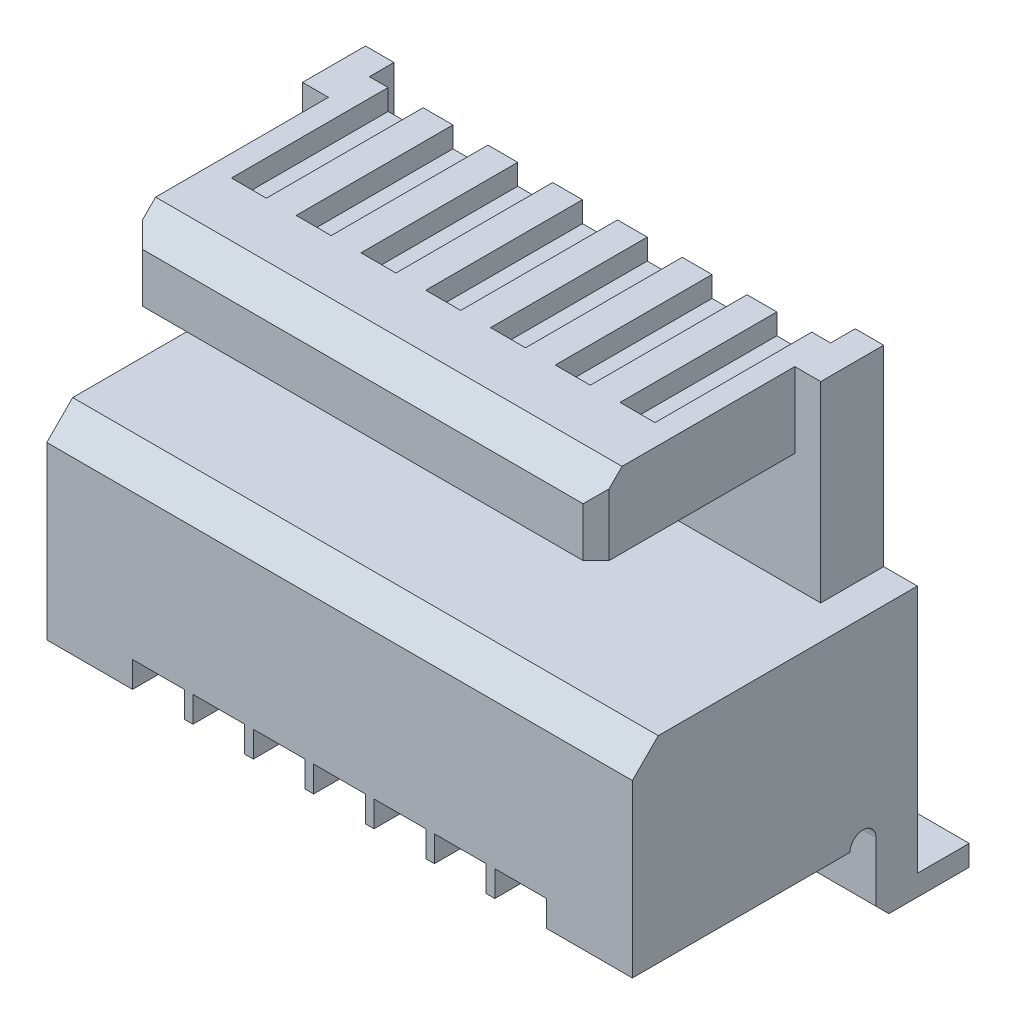
SolidWorks part; units mm, degrees
ref_plane "Front Plane" through (0, 0, 0) normal (0, 0, 1) x (1, 0, 0)
ref_plane "Top Plane" through (0, 0, 0) normal (0, 1, 0) x (1, 0, 0)
ref_plane "Right Plane" through (0, 0, 0) normal (1, 0, 0) x (0, 0, -1)
sketch "Sketch1" plane through (0, 0, 0) normal (0, 1, 0) x (1, 0, 0)
  line L0 (0, 0) -> (0, -11)
  line L1 (0, -11) -> (22.6, -11)
  line L2 (22.6, -11) -> (22.6, 0)
  line L3 (0, 0) -> (2.8, 0)
  line L4 (2.8, 0) -> (2.8, -8.9)
  line L5 (2.8, -8.9) -> (19.8, -8.9)
  line L6 (19.8, -8.9) -> (19.8, 0)
  line L7 (19.8, 0) -> (22.6, 0)
  dimension "D1" = 11
  dimension "D2" = 22.6
  dimension "D3" = 2.8
  dimension "D4" = 2.8
  dimension "D5" = 2.1
  dimension "D6" = 11
extrude "Boss-Extrude1" add sketch "Sketch1" along normal blind 7.6
sketch "Sketch2" plane through (0, 7.6, 0) normal (0, 1, 0) x (1, 0, 0)
  line L0 (2.8, 0) -> (19.8, 0)
  line L1 (2.8, 0) -> (2.8, -8.9)
  line L2 (2.8, -8.9) -> (19.8, -8.9)
  line L3 (19.8, -8.9) -> (19.8, 0)
  line L8 (2.8, 0) -> (0, 0)
  line L9 (0, 0) -> (0, -11)
  line L10 (0, -11) -> (22.6, -11)
  line L11 (22.6, -11) -> (22.6, 0)
  line L12 (22.6, 0) -> (19.8, 0)
  line L13 (19.8, 0) -> (19.8, -8.9)
  line L14 (19.8, -8.9) -> (2.8, -8.9)
  line L15 (2.8, -8.9) -> (2.8, 0)
  line L16 (2.8, 0) -> (0, 0)
  line L17 (0, 0) -> (0, -11)
  line L18 (0, -11) -> (22.6, -11)
  line L19 (22.6, -11) -> (22.6, 0)
  line L20 (22.6, 0) -> (19.8, 0)
  line L21 (19.8, 0) -> (19.8, -8.9)
  line L22 (19.8, -8.9) -> (2.8, -8.9)
  line L23 (2.8, -8.9) -> (2.8, 0)
  line M14 (19.8, 0) -> (19.8, -8.9)
  line M15 (19.8, -8.9) -> (2.8, -8.9)
  line M16 (2.8, -8.9) -> (2.8, 0)
  dimension "D1" = 0
extrude "Boss-Extrude2" add sketch "Sketch2" against normal blind 2 contours L0 M16 M15 M14
sketch "Sketch3" plane through (0, 7.6, 0) normal (0, 1, 0) x (1, 0, 0)
  line L1 (1.3, -2.43) -> (21.3, -2.43)
  line L2 (1.3, -2.43) -> (1.3, 0)
  line L4 (22.6, 0) -> (0, 0)
  line L5 (0, 0) -> (0, -11)
  line L6 (0, -11) -> (22.6, -11)
  line L7 (22.6, -11) -> (22.6, 0)
  line L8 (22.6, 0) -> (0, 0)
  line L9 (0, 0) -> (0, -11)
  line L10 (0, -11) -> (22.6, -11)
  line L11 (22.6, -11) -> (22.6, 0)
  line L12 (21.3, -2.43) -> (21.3, 0)
  line L13 (1.3, -2.43) -> (11.3, 0) construction
  line L14 (11.3, 0) -> (21.3, -2.43) construction
  point P2 (11.3, 0)
  dimension "D2" = 20
  dimension "D3" = 2.43
  dimension "D4" = 10
  dimension "D1" = 0
extrude "Boss-Extrude3" add sketch "Sketch3" along normal blind 7.4 contours L1 L12 L8 L2
sketch "Sketch4" plane through (0, 0, 2.43) normal (0, 0, 1) x (1, 0, 0)
  line L0 (2.3, 15) -> (2.3, 12.1)
  line L1 (2.3, 12.1) -> (20.3, 12.1)
  line L2 (20.3, 12.1) -> (20.3, 15)
  line L4 (1.3, 7.6) -> (21.3, 7.6)
  line L5 (21.3, 7.6) -> (21.3, 15)
  line L6 (21.3, 15) -> (1.3, 15)
  line L7 (1.3, 15) -> (1.3, 7.6)
  line L8 (1.3, 7.6) -> (21.3, 7.6)
  line L9 (21.3, 7.6) -> (21.3, 15)
  line L10 (21.3, 15) -> (1.3, 15)
  line L11 (1.3, 15) -> (1.3, 7.6)
  point P6 (11.3, 15)
  line M10 (21.3, 15) -> (1.3, 15)
  dimension "D2" = 9
  dimension "D3" = 18
  dimension "D4" = 2.9
  dimension "D1" = 0
extrude "Boss-Extrude4" add sketch "Sketch4" along normal blind 7.67 contours L1 L2 L0 M10
sketch "Sketch5" plane through (0, 0, 0) normal (0, 0, -1) x (-1, 0, 0)
  line L0 (-19.8, 5.6) -> (-19.8, 11.5)
  line L1 (-19.8, 11.5) -> (-20.2, 11.5)
  line L2 (-20.2, 11.5) -> (-20.2, 15)
  line L3 (-2.8, 5.6) -> (-2.8, 11.5)
  line L4 (-2.8, 11.5) -> (-2.4, 11.5)
  line L5 (-2.4, 11.5) -> (-2.4, 15)
  line L12 (-22.6, 0) -> (-19.8, 0)
  line L13 (-19.8, 0) -> (-19.8, 5.6)
  line L14 (-19.8, 5.6) -> (-2.8, 5.6)
  line L15 (-2.8, 5.6) -> (-2.8, 0)
  line L16 (-2.8, 0) -> (0, 0)
  line L17 (0, 0) -> (0, 7.6)
  line L18 (0, 7.6) -> (-1.3, 7.6)
  line L19 (-1.3, 7.6) -> (-1.3, 15)
  line L20 (-1.3, 15) -> (-21.3, 15)
  line L21 (-21.3, 15) -> (-21.3, 7.6)
  line L22 (-21.3, 7.6) -> (-22.6, 7.6)
  line L23 (-22.6, 7.6) -> (-22.6, 0)
  line L24 (-22.6, 0) -> (-19.8, 0)
  line L25 (-19.8, 0) -> (-19.8, 5.6)
  line L26 (-19.8, 5.6) -> (-2.8, 5.6)
  line L27 (-2.8, 5.6) -> (-2.8, 0)
  line L28 (-2.8, 0) -> (0, 0)
  line L29 (0, 0) -> (0, 7.6)
  line L30 (0, 7.6) -> (-1.3, 7.6)
  line L31 (-1.3, 7.6) -> (-1.3, 15)
  line L32 (-1.3, 15) -> (-21.3, 15)
  line L33 (-21.3, 15) -> (-21.3, 7.6)
  line L34 (-21.3, 7.6) -> (-22.6, 7.6)
  line L35 (-22.6, 7.6) -> (-22.6, 0)
  line M19 (-19.8, 5.6) -> (-2.8, 5.6)
  line M25 (-1.3, 15) -> (-21.3, 15)
  dimension "D2" = 1.1
  dimension "D3" = 3.5
  dimension "D4" = 1.1
  dimension "D5" = 3.5
  dimension "D1" = 0
extrude "Cut-Extrude1" cut sketch "Sketch5" against normal blind 0.95 contours L4 L5 L2 L1 L0 L3 M25 M19
sketch "Sketch6" plane through (0, 15, 0) normal (0, 1, 0) x (1, 0, 0)
  line L0 (3.125, -0.95) -> (3.125, -7)
  line L1 (3.125, -7) -> (4.475, -7)
  line L2 (4.475, -7) -> (4.475, -0.95)
  line L3 (5.625, -0.95) -> (5.625, -7)
  line L4 (5.625, -7) -> (6.975, -7)
  line L5 (6.975, -7) -> (6.975, -0.95)
  line L6 (8.125, -0.95) -> (8.125, -7)
  line L7 (8.125, -7) -> (9.475, -7)
  line L8 (9.475, -7) -> (9.475, -0.95)
  line L9 (10.625, -0.95) -> (10.625, -7)
  line L10 (10.625, -7) -> (11.975, -7)
  line L11 (11.975, -7) -> (11.975, -0.95)
  line L12 (21.3, 0) -> (20.2, 0)
  line L13 (20.2, 0) -> (20.2, -0.95)
  line L14 (20.2, -0.95) -> (2.4, -0.95)
  line L15 (2.4, -0.95) -> (2.4, 0)
  line L16 (2.4, 0) -> (1.3, 0)
  line L17 (1.3, 0) -> (1.3, -2.43)
  line L18 (1.3, -2.43) -> (2.3, -2.43)
  line L19 (2.3, -2.43) -> (2.3, -10.1)
  line L20 (2.3, -10.1) -> (20.3, -10.1)
  line L21 (20.3, -10.1) -> (20.3, -2.43)
  line L22 (20.3, -2.43) -> (21.3, -2.43)
  line L23 (21.3, -2.43) -> (21.3, 0)
  line L24 (21.3, 0) -> (20.2, 0)
  line L25 (20.2, 0) -> (20.2, -0.95)
  line L26 (20.2, -0.95) -> (2.4, -0.95)
  line L27 (2.4, -0.95) -> (2.4, 0)
  line L28 (2.4, 0) -> (1.3, 0)
  line L29 (1.3, 0) -> (1.3, -2.43)
  line L30 (1.3, -2.43) -> (2.3, -2.43)
  line L31 (2.3, -2.43) -> (2.3, -10.1)
  line L32 (2.3, -10.1) -> (20.3, -10.1)
  line L33 (20.3, -10.1) -> (20.3, -2.43)
  line L34 (20.3, -2.43) -> (21.3, -2.43)
  line L35 (21.3, -2.43) -> (21.3, 0)
  line L36 (13.125, -0.95) -> (13.125, -7)
  line L37 (13.125, -7) -> (14.475, -7)
  line L38 (14.475, -7) -> (14.475, -0.95)
  line L39 (15.625, -0.95) -> (15.625, -7)
  line L40 (15.625, -7) -> (16.975, -7)
  line L41 (16.975, -7) -> (16.975, -0.95)
  line L42 (18.125, -0.95) -> (18.125, -7)
  line L43 (18.125, -7) -> (19.475, -7)
  line L44 (19.475, -7) -> (19.475, -0.95)
  line M18 (20.2, -0.95) -> (2.4, -0.95)
  dimension "D2" = 1.35
  dimension "D3" = 0.825
  dimension "D4" = 7
  dimension "D5" = 7
  dimension "D6" = 0.825
  dimension "D1" = 0
extrude "Cut-Extrude2" cut sketch "Sketch6" against normal blind 0.8 contours L1 L2 L0 M18 | L4 L5 L3 M18 | L7 L8 L6 M18 | L10 L11 L9 M18 | L37 L38 L26 L36 | L40 L41 L26 L39 | L43 L44 L26 L42
chamfer "Chamfer1" distance 0.5 angle 45 2 edges at (20.3, 13.55, 10.1) (2.3, 13.55, 10.1)
chamfer "Chamfer2" distance 1 angle 45 1 edges at (11.3, 15, 10.1)
chamfer "Chamfer3" distance 1 angle 45 1 edges at (11.3, 7.6, 11)
sketch "Sketch7" plane through (0, 0, 0) normal (0, -1, 0) x (1, 0, 0)
  line L0 (0, 1.6) -> (2.8, 1.6)
  line L1 (19.8, 1.6) -> (22.6, 1.6)
  line L8 (0, 0) -> (2.8, 0)
  line L9 (2.8, 0) -> (2.8, 8.9)
  line L10 (2.8, 8.9) -> (19.8, 8.9)
  line L11 (19.8, 8.9) -> (19.8, 0)
  line L12 (19.8, 0) -> (22.6, 0)
  line L13 (22.6, 0) -> (22.6, 11)
  line L14 (22.6, 11) -> (0, 11)
  line L15 (0, 11) -> (0, 0)
  line L16 (0, 0) -> (2.8, 0)
  line L17 (2.8, 0) -> (2.8, 8.9)
  line L18 (2.8, 8.9) -> (19.8, 8.9)
  line L19 (19.8, 8.9) -> (19.8, 0)
  line L20 (19.8, 0) -> (22.6, 0)
  line L21 (22.6, 0) -> (22.6, 11)
  line L22 (22.6, 11) -> (0, 11)
  line L23 (0, 11) -> (0, 0)
  line M10 (0, 0) -> (2.8, 0)
  line M11 (2.8, 0) -> (2.8, 8.9)
  line M13 (19.8, 8.9) -> (19.8, 0)
  line M14 (19.8, 0) -> (22.6, 0)
  line M15 (22.6, 0) -> (22.6, 11)
  line M17 (0, 11) -> (0, 0)
  dimension "D2" = 1.6
  dimension "D1" = 0
extrude "Boss-Extrude5" add sketch "Sketch7" along normal blind 2.8 contours L0 M17 M10 M11 | L1 M13 M14 M15
sketch "Sketch8" plane through (0, 0, 0) normal (0, 0, -1) x (-1, 0, 0)
  line L0 (-22.6, -2) -> (-19.8, -2)
  line L1 (-2.8, -2) -> (0, -2)
  line L8 (-19.8, -2.8) -> (-19.8, 11.5)
  line L9 (-19.8, 11.5) -> (-20.2, 11.5)
  line L10 (-20.2, 11.5) -> (-20.2, 15)
  line L11 (-20.2, 15) -> (-21.3, 15)
  line L12 (-21.3, 15) -> (-21.3, 7.6)
  line L13 (-21.3, 7.6) -> (-22.6, 7.6)
  line L14 (-22.6, 7.6) -> (-22.6, -2.8)
  line L15 (-22.6, -2.8) -> (-19.8, -2.8)
  line L16 (-19.8, -2.8) -> (-19.8, 11.5)
  line L17 (-19.8, 11.5) -> (-20.2, 11.5)
  line L18 (-20.2, 11.5) -> (-20.2, 15)
  line L19 (-20.2, 15) -> (-21.3, 15)
  line L20 (-21.3, 15) -> (-21.3, 7.6)
  line L21 (-21.3, 7.6) -> (-22.6, 7.6)
  line L22 (-22.6, 7.6) -> (-22.6, -2.8)
  line L23 (-22.6, -2.8) -> (-19.8, -2.8)
  line L25 (-2.4, 11.5) -> (-2.8, 11.5)
  line L26 (-2.8, 11.5) -> (-2.8, -2.8)
  line L27 (-2.8, -2.8) -> (0, -2.8)
  line L28 (0, -2.8) -> (0, 7.6)
  line L29 (0, 7.6) -> (-1.3, 7.6)
  line L30 (-1.3, 7.6) -> (-1.3, 15)
  line L31 (-1.3, 15) -> (-2.4, 15)
  line L32 (-2.4, 15) -> (-2.4, 11.5)
  line L33 (-2.4, 11.5) -> (-2.8, 11.5)
  line L34 (-2.8, 11.5) -> (-2.8, -2.8)
  line L35 (-2.8, -2.8) -> (0, -2.8)
  line L36 (0, -2.8) -> (0, 7.6)
  line L37 (0, 7.6) -> (-1.3, 7.6)
  line L38 (-1.3, 7.6) -> (-1.3, 15)
  line L39 (-1.3, 15) -> (-2.4, 15)
  line L40 (-2.4, 15) -> (-2.4, 11.5)
  line M19 (-19.8, -2.8) -> (-19.8, 11.5)
  line M25 (-22.6, 7.6) -> (-22.6, -2.8)
  line M26 (-22.6, -2.8) -> (-19.8, -2.8)
  dimension "D2" = 0.8
  dimension "D4" = 0.8
  dimension "D1" = 0
  dimension "D3" = 0
extrude "Boss-Extrude6" add sketch "Sketch8" along normal blind 2 contours L0 M25 M26 M19 | L35 L36 L1 L34
sketch "Sketch9" plane through (0, 0, 0) normal (-1, 0, 0) x (0, 0, 1)
  line L9 (11, 0) -> (11, 6.6)
  line L10 (11, 6.6) -> (10, 7.6)
  line L11 (10, 7.6) -> (0, 7.6)
  line L12 (0, 7.6) -> (0, -2)
  line L13 (0, -2) -> (-2, -2)
  line L14 (-2, -2) -> (-2, -2.8)
  line L15 (-2, -2.8) -> (1.6, -2.8)
  line L16 (1.6, -2.8) -> (1.6, 0)
  line L17 (1.6, 0) -> (11, 0)
  line L18 (11, 0) -> (11, 6.6)
  line L19 (11, 6.6) -> (10, 7.6)
  line L20 (10, 7.6) -> (0, 7.6)
  line L21 (0, 7.6) -> (0, -2)
  line L22 (0, -2) -> (-2, -2)
  line L23 (-2, -2) -> (-2, -2.8)
  line L24 (-2, -2.8) -> (1.6, -2.8)
  line L25 (1.6, -2.8) -> (1.6, 0)
  line L26 (1.6, 0) -> (11, 0)
  circle A0 centre (2.1, 0) radius 0.5
  line M18 (1.6, 0) -> (11, 0)
  dimension "D2" = 0.5
  dimension "D1" = 0
extrude "Cut-Extrude3" cut sketch "Sketch9" against normal through all contours A0 M18
chamfer "Chamfer4" distance 0.5 angle 45 2 edges at (1.4, -2.8, 1.6) (21.2, -2.8, 1.6)
sketch "Sketch10" plane through (0, 5.6, 0) normal (0, -1, 0) x (1, 0, 0)
  line L0 (5.31, 8.9) -> (5.31, 0.95)
  line L1 (3.31, 8.9) -> (3.31, 0.95)
  line L2 (5.64, 8.9) -> (5.64, 0.95)
  line L3 (7.64, 8.9) -> (7.64, 0.95)
  line L4 (2.8, 0.95) -> (19.8, 0.95)
  line L5 (19.8, 0.95) -> (19.8, 8.9)
  line L6 (19.8, 8.9) -> (2.8, 8.9)
  line L7 (2.8, 8.9) -> (2.8, 0.95)
  line L8 (2.8, 0.95) -> (19.8, 0.95)
  line L9 (19.8, 0.95) -> (19.8, 8.9)
  line L10 (19.8, 8.9) -> (2.8, 8.9)
  line L11 (2.8, 8.9) -> (2.8, 0.95)
  line L12 (7.97, 8.9) -> (7.97, 0.95)
  line L13 (9.97, 8.9) -> (9.97, 0.95)
  line L14 (10.3, 8.9) -> (10.3, 0.95)
  line L15 (12.3, 8.9) -> (12.3, 0.95)
  line L16 (12.63, 8.9) -> (12.63, 0.95)
  line L17 (14.63, 8.9) -> (14.63, 0.95)
  line L18 (14.96, 8.9) -> (14.96, 0.95)
  line L19 (16.96, 8.9) -> (16.96, 0.95)
  line L20 (19.29, 8.9) -> (19.29, 0.95)
  line L21 (17.29, 8.9) -> (17.29, 0.95)
  line L22 (11.3, 8.9) -> (11.3, 0.95) construction
  line M20 (2.8, 0.95) -> (19.8, 0.95)
  line M22 (19.8, 8.9) -> (2.8, 8.9)
  dimension "D2" = 2
  dimension "D3" = 0.33
  dimension "D4" = 2
  dimension "D5" = 0.33
  dimension "D6" = 1
  dimension "D7" = 0.33
  dimension "D8" = 0.33
  dimension "D9" = 0.33
  dimension "D10" = 0.33
  dimension "D11" = 2
  dimension "D12" = 2
  dimension "D13" = 2
  dimension "D14" = 2
  dimension "D15" = 2
  dimension "D1" = 0
extrude "Cut-Extrude4" cut sketch "Sketch10" against normal blind 1 contours L1 L0 M22 M20 | L3 L2 M22 M20 | L13 L10 L12 L8 | L10 L22 L15 M20 | L22 L14 L8 M22 | L17 L10 L16 L8 | L19 L10 L18 L8 | L10 L21 L8 L20
sketch "Sketch11" plane through (0, 0, 8.9) normal (0, 0, -1) x (-1, 0, 0)
  line L0 (-19.29, 5.6) -> (-19.29, 0)
  line L1 (-17.29, 5.6) -> (-17.29, 0)
  line L2 (-16.96, 5.6) -> (-16.96, 0)
  line L3 (-14.96, 5.6) -> (-14.96, 0)
  line L4 (-14.63, 5.6) -> (-14.63, 0)
  line L5 (-12.63, 5.6) -> (-12.63, 0)
  line L6 (-12.3, 5.6) -> (-12.3, 0)
  line L7 (-10.3, 5.6) -> (-10.3, 0)
  line L8 (-9.97, 5.6) -> (-9.97, 0)
  line L9 (-7.97, 5.6) -> (-7.97, 0)
  line L10 (-7.64, 5.6) -> (-7.64, 0)
  line L11 (-5.64, 5.6) -> (-5.64, 0)
  line L12 (-5.31, 5.6) -> (-5.31, 0)
  line L13 (-3.31, 5.6) -> (-3.31, 0)
  line L32 (-19.29, 5.6) -> (-19.8, 5.6)
  line L33 (-19.8, 5.6) -> (-19.8, 0)
  line L34 (-19.8, 0) -> (-2.8, 0)
  line L35 (-2.8, 0) -> (-2.8, 5.6)
  line L36 (-2.8, 5.6) -> (-3.31, 5.6)
  line L37 (-3.31, 5.6) -> (-3.31, 6.6)
  line L38 (-3.31, 6.6) -> (-5.31, 6.6)
  line L39 (-5.31, 6.6) -> (-5.31, 5.6)
  line L40 (-5.31, 5.6) -> (-5.64, 5.6)
  line L41 (-5.64, 5.6) -> (-5.64, 6.6)
  line L42 (-5.64, 6.6) -> (-7.64, 6.6)
  line L43 (-7.64, 6.6) -> (-7.64, 5.6)
  line L44 (-7.64, 5.6) -> (-7.97, 5.6)
  line L45 (-7.97, 5.6) -> (-7.97, 6.6)
  line L46 (-7.97, 6.6) -> (-9.97, 6.6)
  line L47 (-9.97, 6.6) -> (-9.97, 5.6)
  line L48 (-9.97, 5.6) -> (-10.3, 5.6)
  line L49 (-10.3, 5.6) -> (-10.3, 6.6)
  line L50 (-10.3, 6.6) -> (-12.3, 6.6)
  line L51 (-12.3, 6.6) -> (-12.3, 5.6)
  line L52 (-12.3, 5.6) -> (-12.63, 5.6)
  line L53 (-12.63, 5.6) -> (-12.63, 6.6)
  line L54 (-12.63, 6.6) -> (-14.63, 6.6)
  line L55 (-14.63, 6.6) -> (-14.63, 5.6)
  line L56 (-14.63, 5.6) -> (-14.96, 5.6)
  line L57 (-14.96, 5.6) -> (-14.96, 6.6)
  line L58 (-14.96, 6.6) -> (-16.96, 6.6)
  line L59 (-16.96, 6.6) -> (-16.96, 5.6)
  line L60 (-16.96, 5.6) -> (-17.29, 5.6)
  line L61 (-17.29, 5.6) -> (-17.29, 6.6)
  line L62 (-17.29, 6.6) -> (-19.29, 6.6)
  line L63 (-19.29, 6.6) -> (-19.29, 5.6)
  line L64 (-19.29, 5.6) -> (-19.8, 5.6)
  line L65 (-19.8, 5.6) -> (-19.8, 0)
  line L66 (-19.8, 0) -> (-2.8, 0)
  line L67 (-2.8, 0) -> (-2.8, 5.6)
  line L68 (-2.8, 5.6) -> (-3.31, 5.6)
  line L69 (-3.31, 5.6) -> (-3.31, 6.6)
  line L70 (-3.31, 6.6) -> (-5.31, 6.6)
  line L71 (-5.31, 6.6) -> (-5.31, 5.6)
  line L72 (-5.31, 5.6) -> (-5.64, 5.6)
  line L73 (-5.64, 5.6) -> (-5.64, 6.6)
  line L74 (-5.64, 6.6) -> (-7.64, 6.6)
  line L75 (-7.64, 6.6) -> (-7.64, 5.6)
  line L76 (-7.64, 5.6) -> (-7.97, 5.6)
  line L77 (-7.97, 5.6) -> (-7.97, 6.6)
  line L78 (-7.97, 6.6) -> (-9.97, 6.6)
  line L79 (-9.97, 6.6) -> (-9.97, 5.6)
  line L80 (-9.97, 5.6) -> (-10.3, 5.6)
  line L81 (-10.3, 5.6) -> (-10.3, 6.6)
  line L82 (-10.3, 6.6) -> (-12.3, 6.6)
  line L83 (-12.3, 6.6) -> (-12.3, 5.6)
  line L84 (-12.3, 5.6) -> (-12.63, 5.6)
  line L85 (-12.63, 5.6) -> (-12.63, 6.6)
  line L86 (-12.63, 6.6) -> (-14.63, 6.6)
  line L87 (-14.63, 6.6) -> (-14.63, 5.6)
  line L88 (-14.63, 5.6) -> (-14.96, 5.6)
  line L89 (-14.96, 5.6) -> (-14.96, 6.6)
  line L90 (-14.96, 6.6) -> (-16.96, 6.6)
  line L91 (-16.96, 6.6) -> (-16.96, 5.6)
  line L92 (-16.96, 5.6) -> (-17.29, 5.6)
  line L93 (-17.29, 5.6) -> (-17.29, 6.6)
  line L94 (-17.29, 6.6) -> (-19.29, 6.6)
  line L95 (-19.29, 6.6) -> (-19.29, 5.6)
  line M35 (-19.8, 0) -> (-2.8, 0)
  line M38 (-3.31, 5.6) -> (-3.31, 6.6)
  line M39 (-3.31, 6.6) -> (-5.31, 6.6)
  line M40 (-5.31, 6.6) -> (-5.31, 5.6)
  line M42 (-5.64, 5.6) -> (-5.64, 6.6)
  line M43 (-5.64, 6.6) -> (-7.64, 6.6)
  line M44 (-7.64, 6.6) -> (-7.64, 5.6)
  line M46 (-7.97, 5.6) -> (-7.97, 6.6)
  line M47 (-7.97, 6.6) -> (-9.97, 6.6)
  line M48 (-9.97, 6.6) -> (-9.97, 5.6)
  line M50 (-10.3, 5.6) -> (-10.3, 6.6)
  line M51 (-10.3, 6.6) -> (-12.3, 6.6)
  line M52 (-12.3, 6.6) -> (-12.3, 5.6)
  line M54 (-12.63, 5.6) -> (-12.63, 6.6)
  line M55 (-12.63, 6.6) -> (-14.63, 6.6)
  line M56 (-14.63, 6.6) -> (-14.63, 5.6)
  line M58 (-14.96, 5.6) -> (-14.96, 6.6)
  line M59 (-14.96, 6.6) -> (-16.96, 6.6)
  line M60 (-16.96, 6.6) -> (-16.96, 5.6)
  line M62 (-17.29, 5.6) -> (-17.29, 6.6)
  line M63 (-17.29, 6.6) -> (-19.29, 6.6)
  line M64 (-19.29, 6.6) -> (-19.29, 5.6)
  dimension "D1" = 0
extrude "Cut-Extrude5" cut sketch "Sketch11" against normal blind 1 contours L1 L0 M62 M63 M64 M35 | L3 L2 M58 M59 M60 M35 | L5 L4 M54 M55 M56 M35 | L7 L6 M50 M51 M52 M35 | L9 L8 M46 M47 M48 M35 | L11 L10 M42 M43 M44 M35 | L13 L12 M38 M39 M40 M35
sketch "Sketch12" plane through (0, 0, 0) normal (0, -1, 0) x (1, 0, 0)
  line L0 (3.31, 9.9) -> (3.31, 11)
  line L1 (5.31, 9.9) -> (5.31, 11)
  line L2 (5.64, 9.9) -> (5.64, 11)
  line L3 (7.64, 9.9) -> (7.64, 11)
  line L4 (7.97, 9.9) -> (7.97, 11)
  line L5 (9.97, 9.9) -> (9.97, 11)
  line L6 (10.3, 9.9) -> (10.3, 11)
  line L7 (12.3, 9.9) -> (12.3, 11)
  line L8 (12.63, 9.9) -> (12.63, 11)
  line L9 (14.63, 9.9) -> (14.63, 11)
  line L10 (14.96, 9.9) -> (14.96, 11)
  line L11 (16.96, 9.9) -> (16.96, 11)
  line L12 (17.29, 9.9) -> (17.29, 11)
  line L13 (19.29, 9.9) -> (19.29, 11)
  line L36 (16.96, 8.9) -> (17.29, 8.9)
  line L37 (17.29, 8.9) -> (17.29, 9.9)
  line L38 (17.29, 9.9) -> (19.29, 9.9)
  line L39 (19.29, 9.9) -> (19.29, 8.9)
  line L40 (19.29, 8.9) -> (19.8, 8.9)
  line L41 (19.8, 8.9) -> (19.8, 2.6)
  line L42 (19.8, 2.6) -> (22.6, 2.6)
  line L43 (22.6, 2.6) -> (22.6, 11)
  line L44 (22.6, 11) -> (0, 11)
  line L45 (0, 11) -> (0, 2.6)
  line L46 (0, 2.6) -> (2.8, 2.6)
  line L47 (2.8, 2.6) -> (2.8, 8.9)
  line L48 (2.8, 8.9) -> (3.31, 8.9)
  line L49 (3.31, 8.9) -> (3.31, 9.9)
  line L50 (3.31, 9.9) -> (5.31, 9.9)
  line L51 (5.31, 9.9) -> (5.31, 8.9)
  line L52 (5.31, 8.9) -> (5.64, 8.9)
  line L53 (5.64, 8.9) -> (5.64, 9.9)
  line L54 (5.64, 9.9) -> (7.64, 9.9)
  line L55 (7.64, 9.9) -> (7.64, 8.9)
  line L56 (7.64, 8.9) -> (7.97, 8.9)
  line L57 (7.97, 8.9) -> (7.97, 9.9)
  line L58 (7.97, 9.9) -> (9.97, 9.9)
  line L59 (9.97, 9.9) -> (9.97, 8.9)
  line L60 (9.97, 8.9) -> (10.3, 8.9)
  line L61 (10.3, 8.9) -> (10.3, 9.9)
  line L62 (10.3, 9.9) -> (12.3, 9.9)
  line L63 (12.3, 9.9) -> (12.3, 8.9)
  line L64 (12.3, 8.9) -> (12.63, 8.9)
  line L65 (12.63, 8.9) -> (12.63, 9.9)
  line L66 (12.63, 9.9) -> (14.63, 9.9)
  line L67 (14.63, 9.9) -> (14.63, 8.9)
  line L68 (14.63, 8.9) -> (14.96, 8.9)
  line L69 (14.96, 8.9) -> (14.96, 9.9)
  line L70 (14.96, 9.9) -> (16.96, 9.9)
  line L71 (16.96, 9.9) -> (16.96, 8.9)
  line L72 (16.96, 8.9) -> (17.29, 8.9)
  line L73 (17.29, 8.9) -> (17.29, 9.9)
  line L74 (17.29, 9.9) -> (19.29, 9.9)
  line L75 (19.29, 9.9) -> (19.29, 8.9)
  line L76 (19.29, 8.9) -> (19.8, 8.9)
  line L77 (19.8, 8.9) -> (19.8, 2.6)
  line L78 (19.8, 2.6) -> (22.6, 2.6)
  line L79 (22.6, 2.6) -> (22.6, 11)
  line L80 (22.6, 11) -> (0, 11)
  line L81 (0, 11) -> (0, 2.6)
  line L82 (0, 2.6) -> (2.8, 2.6)
  line L83 (2.8, 2.6) -> (2.8, 8.9)
  line L84 (2.8, 8.9) -> (3.31, 8.9)
  line L85 (3.31, 8.9) -> (3.31, 9.9)
  line L86 (3.31, 9.9) -> (5.31, 9.9)
  line L87 (5.31, 9.9) -> (5.31, 8.9)
  line L88 (5.31, 8.9) -> (5.64, 8.9)
  line L89 (5.64, 8.9) -> (5.64, 9.9)
  line L90 (5.64, 9.9) -> (7.64, 9.9)
  line L91 (7.64, 9.9) -> (7.64, 8.9)
  line L92 (7.64, 8.9) -> (7.97, 8.9)
  line L93 (7.97, 8.9) -> (7.97, 9.9)
  line L94 (7.97, 9.9) -> (9.97, 9.9)
  line L95 (9.97, 9.9) -> (9.97, 8.9)
  line L96 (9.97, 8.9) -> (10.3, 8.9)
  line L97 (10.3, 8.9) -> (10.3, 9.9)
  line L98 (10.3, 9.9) -> (12.3, 9.9)
  line L99 (12.3, 9.9) -> (12.3, 8.9)
  line L100 (12.3, 8.9) -> (12.63, 8.9)
  line L101 (12.63, 8.9) -> (12.63, 9.9)
  line L102 (12.63, 9.9) -> (14.63, 9.9)
  line L103 (14.63, 9.9) -> (14.63, 8.9)
  line L104 (14.63, 8.9) -> (14.96, 8.9)
  line L105 (14.96, 8.9) -> (14.96, 9.9)
  line L106 (14.96, 9.9) -> (16.96, 9.9)
  line L107 (16.96, 9.9) -> (16.96, 8.9)
  line M39 (17.29, 9.9) -> (19.29, 9.9)
  line M45 (22.6, 11) -> (0, 11)
  line M51 (3.31, 9.9) -> (5.31, 9.9)
  line M55 (5.64, 9.9) -> (7.64, 9.9)
  line M59 (7.97, 9.9) -> (9.97, 9.9)
  line M63 (10.3, 9.9) -> (12.3, 9.9)
  line M67 (12.63, 9.9) -> (14.63, 9.9)
  line M71 (14.96, 9.9) -> (16.96, 9.9)
  dimension "D1" = 0
extrude "Cut-Extrude6" cut sketch "Sketch12" against normal blind 1 contours L1 L0 M51 M45 | L3 L2 M55 M45 | L5 L4 M59 M45 | L7 L6 M63 M45 | L9 L8 M67 M45 | L11 L10 M71 M45 | L13 L12 M39 M45
